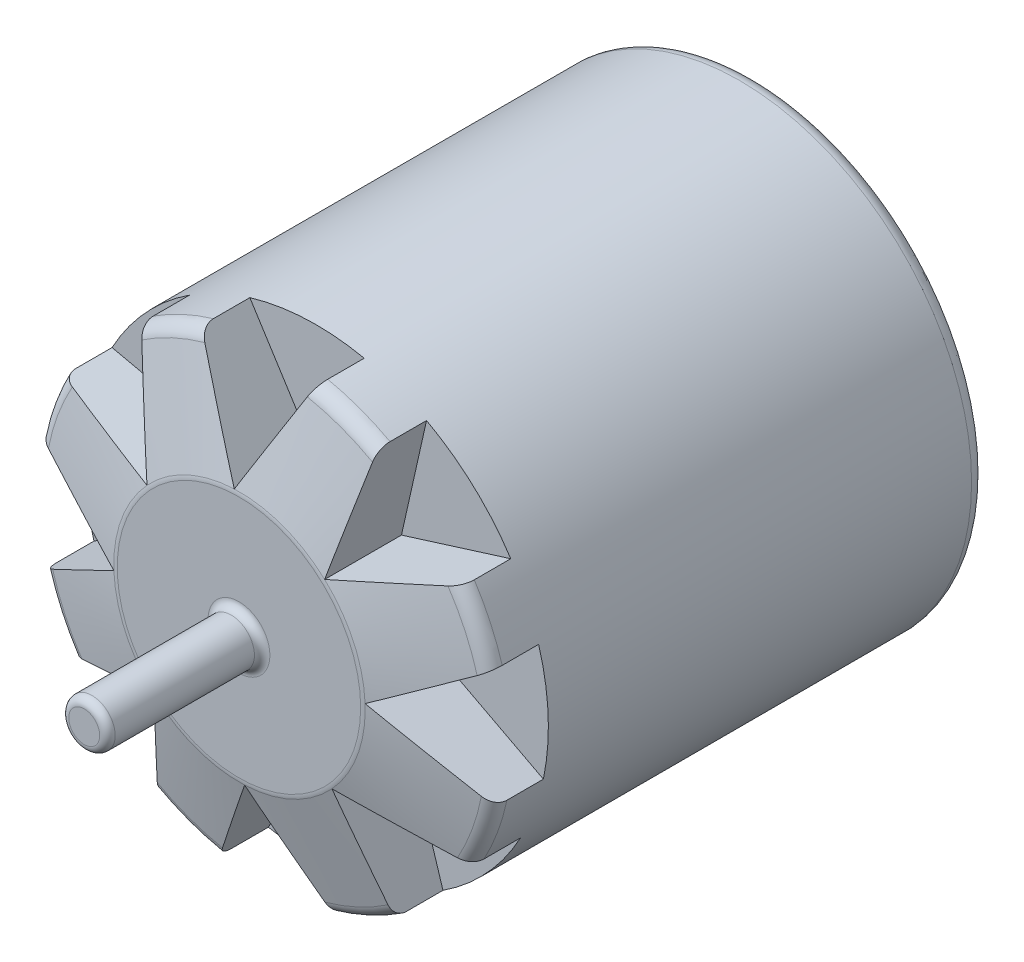
SolidWorks part; units mm, degrees
ref_plane "Front Plane" through (0, 0, 0) normal (0, 0, 1) x (1, 0, 0)
ref_plane "Top Plane" through (0, 0, 0) normal (0, 1, 0) x (1, 0, 0)
ref_plane "Right Plane" through (0, 0, 0) normal (1, 0, 0) x (0, 0, -1)
sketch "Sketch1" plane through (0, 0, 0) normal (0, 0, 1) x (1, 0, 0)
  circle A0 centre (0, 0) radius 15
  dimension "D1" = 30
extrude "Boss-Extrude1" add sketch "Sketch1" along normal blind 35
chamfer "Chamfer1" distance 7 angle 15 1 edges at (15, 0, 0)
fillet "Fillet1" radius 1 2 edges at (15, 0, 1.8756) (8, 0, 0)
sketch "Sketch2" plane through (0, 0, 35) normal (0, 0, 1) x (1, 0, 0)
  circle A0 centre (0, 0) radius 1.5
extrude "Boss-Extrude2" add sketch "Sketch2" along normal blind 10
chamfer "Chamfer2" distance 7 angle 15 1 edges at (15, 0, 35)
fillet "Fillet2" radius 1 2 edges at (8, 0, 35) (15, 0, 33.1244)
sketch "Sketch3" plane through (0, 0, 35) normal (0, 0, 1) x (1, 0, 0)
  line L28 (-0.3348, 8.1203) -> (-4.296, 14.3716)
  line L30 (3.0984, 14.6765) -> (-0.3348, 8.1203)
  line L31 (12.5688, 8.1869) -> (5.5052, 5.9786)
  line L32 (5.5052, 5.9786) -> (7.1245, 13.2)
  line L33 (14.6765, -3.0984) -> (8.1203, 0.3348)
  line L34 (8.1203, 0.3348) -> (14.3716, 4.296)
  line L35 (8.1869, -12.5688) -> (5.9786, -5.5052)
  line L36 (5.9786, -5.5052) -> (13.2, -7.1245)
  line L37 (-3.0984, -14.6765) -> (0.3348, -8.1203)
  line L38 (0.3348, -8.1203) -> (4.296, -14.3716)
  line L39 (-12.5688, -8.1869) -> (-5.5052, -5.9786)
  line L40 (-5.5052, -5.9786) -> (-7.1245, -13.2)
  line L41 (-14.6765, 3.0984) -> (-8.1203, -0.3348)
  line L42 (-8.1203, -0.3348) -> (-14.3716, -4.296)
  line L43 (-8.1869, 12.5688) -> (-5.9786, 5.5052)
  line L44 (-5.9786, 5.5052) -> (-13.2, 7.1245)
  circle A0 centre (0, 0) radius 8.1272 construction
  circle A1 centre (0, 0) radius 15 construction
  arc A2 (7.1245, 13.2) -> (12.5688, 8.1869) centre (0, 0) cw
  arc A3 (14.3716, 4.296) -> (14.6765, -3.0984) centre (0, 0) cw
  arc A16 (-4.296, 14.3716) -> (3.0984, 14.6765) centre (0, 0) cw
  arc A17 (13.2, -7.1245) -> (8.1869, -12.5688) centre (0, 0) cw
  arc A18 (4.296, -14.3716) -> (-3.0984, -14.6765) centre (0, 0) cw
  arc A19 (-7.1245, -13.2) -> (-12.5688, -8.1869) centre (0, 0) cw
  arc A20 (-14.3716, -4.296) -> (-14.6765, 3.0984) centre (0, 0) cw
  arc A21 (-13.2, 7.1245) -> (-8.1869, 12.5688) centre (0, 0) cw
  dimension "D1" = 60
extrude "Cut-Extrude2" cut sketch "Sketch3" against normal blind 5
fillet "Fillet4" radius 0.5 1 edges at (1.5, 0, 45)
fillet "Fillet5" radius 0.5 1 edges at (1.5, 0, 35)
